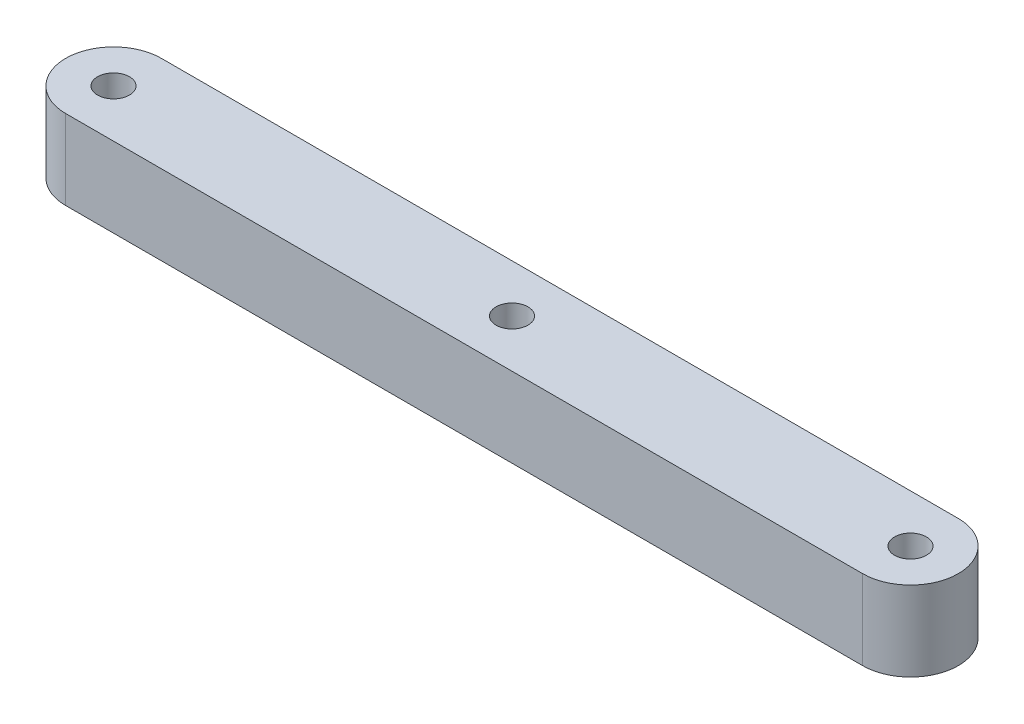
SolidWorks part; units mm, degrees
ref_plane "Front Plane" through (0, 0, 0) normal (0, 0, 1) x (1, 0, 0)
ref_plane "Top Plane" through (0, 0, 0) normal (0, 1, 0) x (1, 0, 0)
ref_plane "Right Plane" through (0, 0, 0) normal (1, 0, 0) x (0, 0, -1)
sketch "Sketch3" plane through (0, 0, 0) normal (0, 1, 0) x (1, 0, 0)
  line L0 (-63.5, 0) -> (63.5, 0) construction
  line L1 (-6.985, 0) -> (6.985, 0) construction
  line L2 (-63.5, 7.62) -> (63.5, 7.62)
  line L3 (-63.5, -7.62) -> (63.5, -7.62)
  arc A0 (-63.5, 7.62) -> (-63.5, -7.62) centre (-63.5, 0) ccw
  arc A1 (63.5, -7.62) -> (63.5, 7.62) centre (63.5, 0) ccw
  point P5 (0, 0)
  dimension "D2" = 7.62
  dimension "D1" = 127
  dimension "D3" = 63.5
extrude "Boss-Extrude1" add sketch "Sketch3" along normal blind 12.7
sketch "Sketch4" plane through (0, 12.7, 0) normal (0, 1, 0) x (1, 0, 0)
  line L0 (0, -6.985) -> (0, 6.985) construction
  circle A0 centre (-63.5, 0) radius 2.54
  circle A1 centre (63.5, 0) radius 2.54
  circle A2 centre (0, 0) radius 2.54
  dimension "D1" = 5.08
  dimension "D2" = 5.08
extrude "Cut-Extrude3" cut sketch "Sketch4" against normal through all
equation "\"TibiaLength\"= 5in"
equation "\"TibiaRadius\"= 0.3in"
equation "\"TibiaDistFromCentre\"= \"TibiaLength\" / 2"
equation "\"TibiaThickness\"= 0.5in"
equation "\"HoleRadius\"= 0.2in"
equation "\"D1@Sketch3\"= \"TibiaLength\""
equation "\"D2@Sketch3\"= \"TibiaRadius\""
equation "\"D3@Sketch3\"= \"TibiaDistFromCentre\""
equation "\"D1@Boss-Extrude1\"= \"TibiaThickness\""
equation "\"D1@Sketch4\"= \"HoleRadius\""
equation "\"D2@Sketch4\"=\"HoleRadius\""
